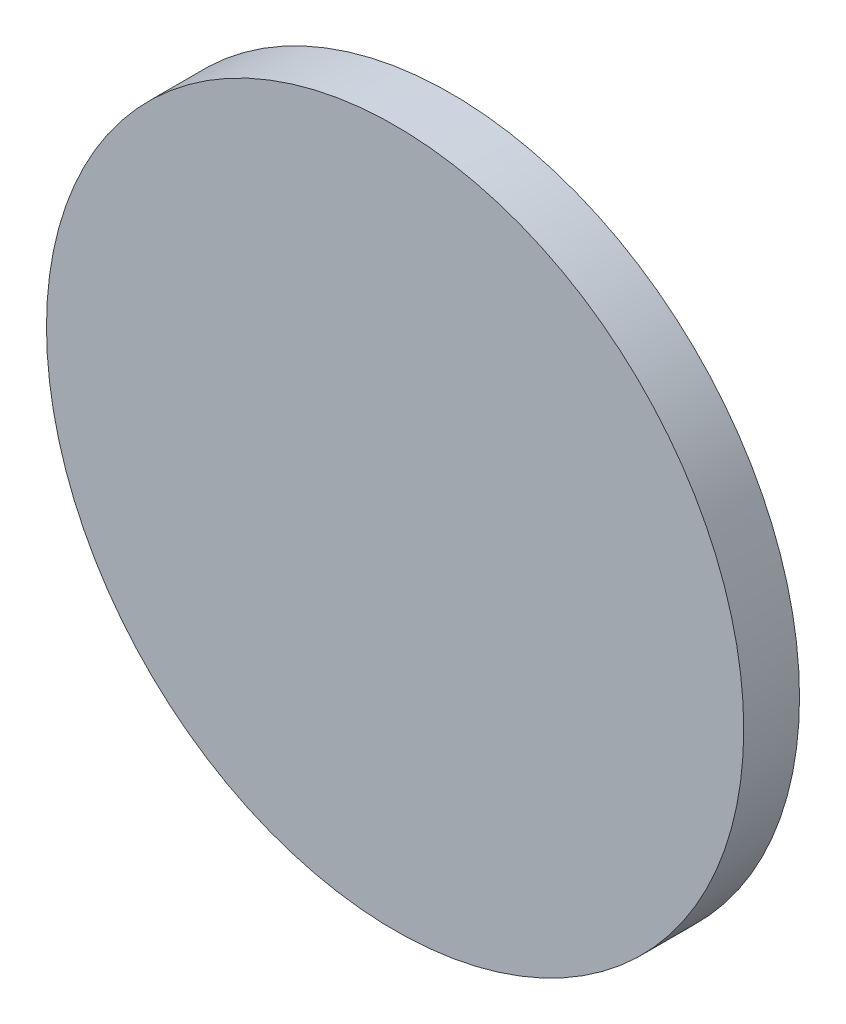
SolidWorks part; units mm, degrees
ref_plane "Front Plane" through (0, 0, 0) normal (0, 0, 1) x (1, 0, 0)
ref_plane "Top Plane" through (0, 0, 0) normal (0, 1, 0) x (1, 0, 0)
ref_plane "Right Plane" through (0, 0, 0) normal (1, 0, 0) x (0, 0, -1)
sketch "Sketch1" plane through (0, 0, 0) normal (0, 0, 1) x (1, 0, 0)
  circle A0 centre (0, 0) radius 6.25
  dimension "D1" = 12.5
extrude "Boss-Extrude1" add sketch "Sketch1" along normal blind 1
